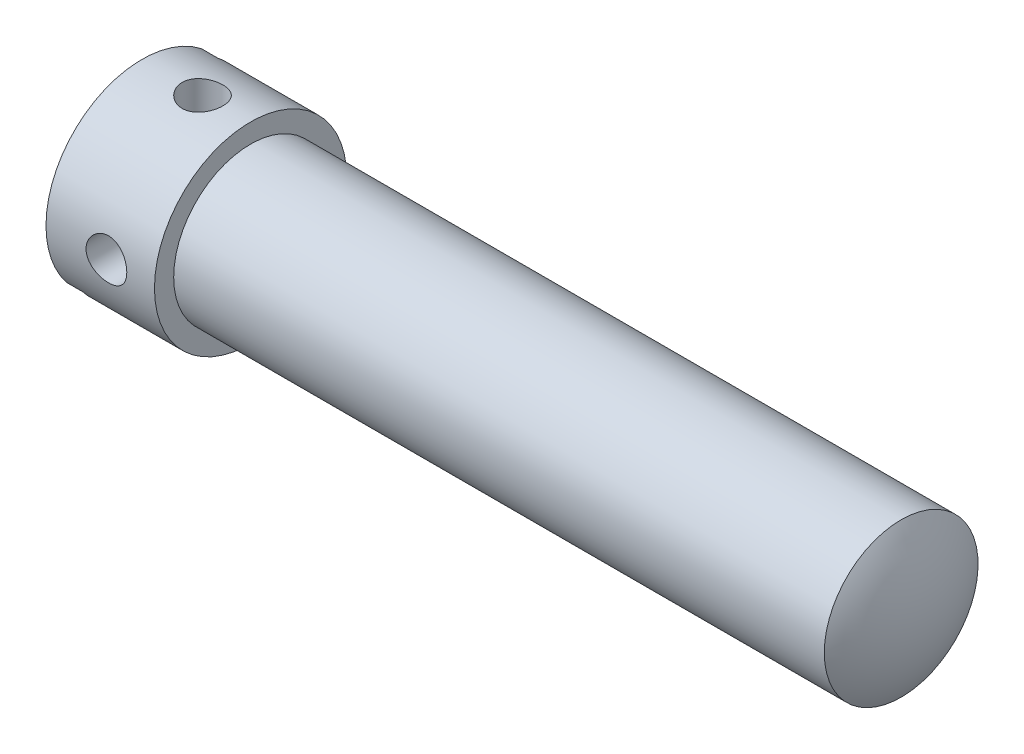
SolidWorks part; units mm, degrees
ref_plane "Front" through (0, 0, 0) normal (0, 0, 1) x (1, 0, 0)
ref_plane "Top" through (0, 0, 0) normal (0, 1, 0) x (1, 0, 0)
ref_plane "Right" through (0, 0, 0) normal (1, 0, 0) x (0, 0, -1)
sketch "Sketch1" plane through (0, 0, 0) normal (0, 0, 1) x (1, 0, 0)
  line L0 (-25.0595, 0) -> (22.8592, 0) construction
  line L1 (0.8579, 5) -> (6.5, 5)
  line L2 (0, 0) -> (6.5, 0)
  line L4 (6.5, 5) -> (6.5, 0)
  arc A0 (0.8579, 5) -> (0, 0) centre (15, 0) ccw
  dimension "R" = 15
  dimension "k" = 6.5
  dimension "dk" = 10
revolve "BaseHead" add sketch "Sketch1" angle 360 about L0
sketch "Sketch2" plane through (6.5, 3.6143, 0.1956) normal (1, 0, 0) x (0, 0, -1)
  circle A0 centre (0.1956, -3.6143) radius 4
  dimension "d" = 8
extrude "Neck" add sketch "Sketch2" along normal blind 35
cosmetic thread "ThreadCosmetic1" [suppressed] parameters "D1"=35, "D2"=4.134
sketch "Sketch3" plane through (41.5, 0.8938, 2.2293) normal (1, 0, 0) x (0, 0, -1)
  circle A0 centre (2.2293, -0.8938) radius 5
  dimension "d" = 10
sketch "Sketch4" plane through (0, 0, 0) normal (0, 0, 1) x (1, 0, 0)
  line L0 (61.4142, 0) -> (-35.076, 0) construction
  line L1 (41.5, -5) -> (41.5, 5) construction
  line L3 (41.5, 0) -> (41.5, 5) construction
  line L4 (34, 7.5) -> (34, 12.5)
  line L5 (34, 12.5) -> (46.5, 12.5)
  line L6 (46.5, 12.5) -> (46.5, 0)
  line L7 (46.5, 0) -> (41.5, 0)
  arc A0 (41.5, 0) -> (34, 7.5) centre (34, 0) ccw
  dimension "D3" = 7.5
  dimension "D1" = 5
  dimension "D2" = 5
revolve "Cut-Revolve1" cut sketch "Sketch4" angle 360 about L0
sketch "Sketch5" plane through (0, 0, 0) normal (0, 0, 1) x (1, 0, 0)
  line L0 (6.5, -5) -> (6.5, 5) construction
  circle A0 centre (4, 0) radius 1.06
extrude "Cut-Extrude1" cut sketch "Sketch5" against normal mid plane 140
sketch "Sketch6" plane through (0, 0, 0) normal (0, 1, 0) x (1, 0, 0)
  line L0 (6.5, -5) -> (6.5, 5) construction
  circle A0 centre (4, 0) radius 1.06
extrude "Cut-Extrude2" cut sketch "Sketch6" against normal mid plane 140
ref_plane "Plane1" through (0, 0, 0) normal (0, -0.7071, 0.7071) x (1, 0, 0)
sketch "Sketch7" plane through (0, 0, 0) normal (0, -0.7071, 0.7071) x (1, 0, 0)
  line L0 (0, 0) -> (-23.3893, 0) construction
  line L1 (0, 0.6) -> (1.7, 0.6)
  line L2 (0, 0.6) -> (0, -0.6)
  line L3 (0, -0.6) -> (1.7, -0.6)
  line L4 (1.7, 0.6) -> (1.7, -0.6)
  line L6 (0.8579, 5) -> (0.8579, -5) construction
  arc A1 (0, 0) -> (0.8579, -6.4929) centre (25, 0) ccw construction
extrude "Cut-Extrude3" cut sketch "Sketch7" against normal mid plane 140
sketch "Sketch8" plane through (0, 0, 0) normal (0, 1, 0) x (1, 0, 0)
  line L0 (0, 0) -> (-28.8801, 0) construction
  line L2 (0, 0.6) -> (1.7, 0.6)
  line L3 (0, 0.6) -> (0, -0.6)
  line L4 (0, -0.6) -> (1.7, -0.6)
  line L5 (1.7, 0.6) -> (1.7, -0.6)
extrude "Cut-Extrude4" [suppressed] cut sketch "Sketch8" against normal mid plane 140
sketch "Sketch9" plane through (0, 0, 0) normal (0, 0, 1) x (1, 0, 0)
  line L0 (40.3443, 2.326) -> (41.3108, 4)
  line L1 (41.3108, 4) -> (41.3108, 5.933)
  line L2 (41.3108, 5.933) -> (39.3778, 5.933)
  line L3 (39.3778, 5.933) -> (39.3778, 4)
  line L4 (39.3778, 4) -> (40.3443, 2.326)
  line L5 (0, 0) -> (68.448, 0) construction
  line L7 (40.3443, 4) -> (40.3443, -4) construction
  dimension "D1" = 8
  dimension "D2" = 1.933
revolve "Cut-Revolve10" [suppressed] cut sketch "Sketch9" angle 360 about L5
pattern_linear "LPattern10" [suppressed] count 15 spacing 2.3196 along (1, 0, 0)
scale "缩放比例1" scale about centroid uniform scaling yes scale factor 1.5
equation "\"D3@Sketch4\" = \"R@Sketch1\"  / 2"
equation "\"D1@Sketch9\" = \"d@Sketch2\""
equation "\"D2@Sketch9\" =  ( \"d@Sketch2\" - \"D2@ThreadCosmetic1\" )  / 2"
equation "\"D3@LPattern10\" = \"D2@Sketch9\" * 1.2"
equation "\"D1@LPattern10\" = \"D1@ThreadCosmetic1\" / \"D3@LPattern10\""
